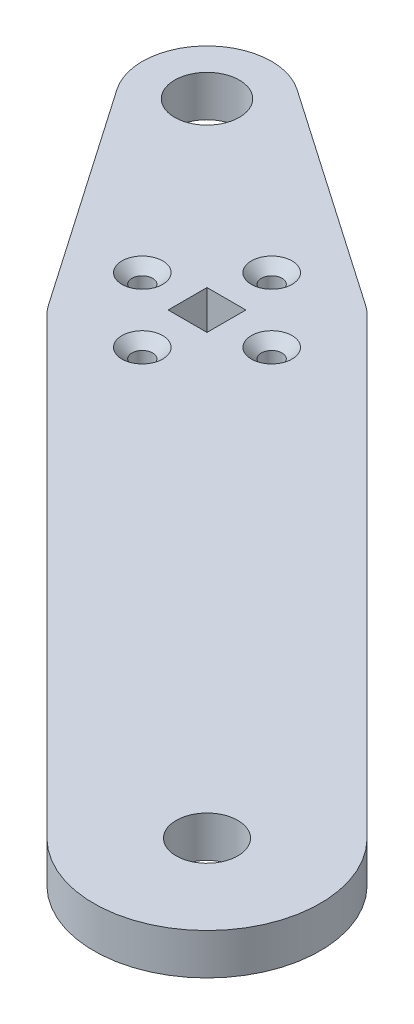
SolidWorks part; units mm, degrees
other "Markup1"
sketch "Sketch6" plane through (50.3553, 0, 50.3553) normal (0.291, 0.9567, 0.0091) x (0.9567, -0.291, -0.0015)
material "6061 Alloy"
ref_plane "Front Plane" through (0, 0, 0) normal (0, 0, 1) x (1, 0, 0)
ref_plane "Top Plane" through (0, 0, 0) normal (0, 1, 0) x (1, 0, 0)
ref_plane "Right Plane" through (0, 0, 0) normal (1, 0, 0) x (0, 0, -1)
sketch "Sketch2" plane through (0, 0, 0) normal (0, 1, 0) x (1, 0, 0)
  line L0 (0, 0) -> (70.7107, -70.7107) construction
  line L1 (-3.005, 3.005) -> (3.005, 3.005)
  line L2 (-3.005, 3.005) -> (-3.005, -3.005)
  line L3 (-3.005, -3.005) -> (3.005, -3.005)
  line L4 (3.005, 3.005) -> (3.005, -3.005)
  line L5 (0, 0) -> (70.7107, 0) construction
  line L6 (-12.3744, -12.3744) -> (12.3744, 12.3744) construction
  line L7 (12.3744, 12.3744) -> (83.085, -58.3363)
  line L8 (-12.3744, -12.3744) -> (58.3363, -83.085)
  line L9 (0, 0) -> (-28.2843, 28.2843) construction
  line L11 (-22.6042, 36.5145) -> (12.3744, 12.3744)
  line L12 (-36.5145, 22.6042) -> (-12.3744, -12.3744)
  circle A0 centre (70.7107, -70.7107) radius 4.7625
  arc A2 (83.085, -58.3363) -> (58.3363, -83.085) centre (70.7107, -70.7107) cw
  circle A3 centre (0, 10) radius 1.5 construction
  circle A4 centre (-10, 0) radius 1.5 construction
  circle A5 centre (0, 0) radius 10 construction
  circle A8 centre (70.7107, -70.7107) radius 37 construction
  circle A9 centre (10, 0) radius 1.5 construction
  circle A10 centre (0, -10) radius 1.5 construction
  arc A11 (-22.6042, 36.5145) -> (-36.5145, 22.6042) centre (-28.2843, 28.2843) ccw
  circle A12 centre (-28.2843, 28.2843) radius 5
  point P4 (0, 3.005)
  point P6 (3.005, 0)
  point P13 (0, 0)
  dimension "D4" = 9.525
  dimension "D5" = 17.5
  dimension "D6" = 40
  dimension "D7" = 3
  dimension "D8" = 20
  dimension "D9" = 74
  dimension "D10" = 10
  dimension "D11" = 10
  dimension "D1" = 6.01
  dimension "D2" = 45
  dimension "D3" = 100
extrude "Boss-Extrude1" add sketch "Sketch2" against normal blind 6.35 contours L8 A2 L7
hole_wizard "CSK for M3 Flat Head Machine Screw1" positions "3DSketch1" profile "Sketch3" countersink size "M3" standard "ANSI Metric" end condition up to next
sketch3d "3DSketch1"
  point P0 (0, 0, -10)
  point P2 (-10, 0, 0)
  point P4 (10, 0, 0)
  point P13 (0, 0, 10)
sketch "Sketch3" plane through (0, 0, -10) normal (1, 0, 0) x (0, 0, 1)
  line L0 (0, 0) -> (0, 6.35)
  line L1 (0, 6.35) -> (1.6, 6.35)
  line L2 (1.6, 6.35) -> (1.6, 1.55)
  line L3 (1.6, 1.55) -> (3.15, 0)
  line L5 (3.15, 0) -> (0, 0)
  line L6 (-1.6, 1.55) -> (-3.15, 0) construction
  line L11 (0, -6.35) -> (0, 107.95) construction
  dimension "Thru Hole Dia." = 3.2
  dimension "Thru Hole Depth" = 6.35
  dimension "Near C'Sink Dia." = 6.3
  dimension "Near C'Sink Angle" = 90
fillet "Fillet1" radius 10 2 edges at (-12.3744, -3.175, 12.3744) (12.3744, -3.175, -12.3744)
